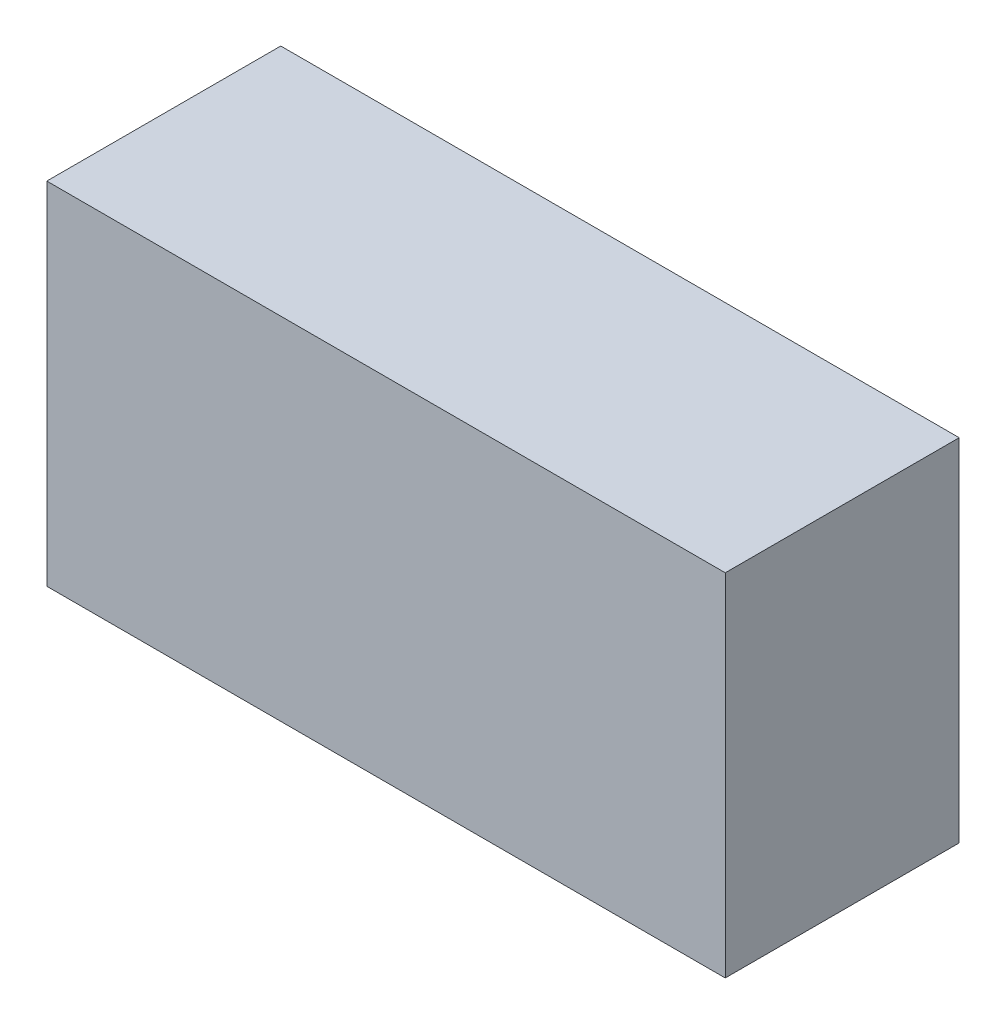
SolidWorks part; units mm, degrees
ref_plane "前视基准面" through (0, 0, 0) normal (0, 0, 1) x (1, 0, 0)
ref_plane "上视基准面" through (0, 0, 0) normal (0, 1, 0) x (1, 0, 0)
ref_plane "右视基准面" through (0, 0, 0) normal (1, 0, 0) x (0, 0, -1)
other "Configuration Table"
sketch "草图1" plane through (0, 0, 0) normal (0, 0, 1) x (1, 0, 0)
  line L1 (-29, -15) -> (29, -15)
  line L2 (-29, -15) -> (-29, 15)
  line L3 (-29, 15) -> (29, 15)
  line L4 (29, -15) -> (29, 15)
extrude "凸台-拉伸1" add sketch "草图1" against normal blind 20
